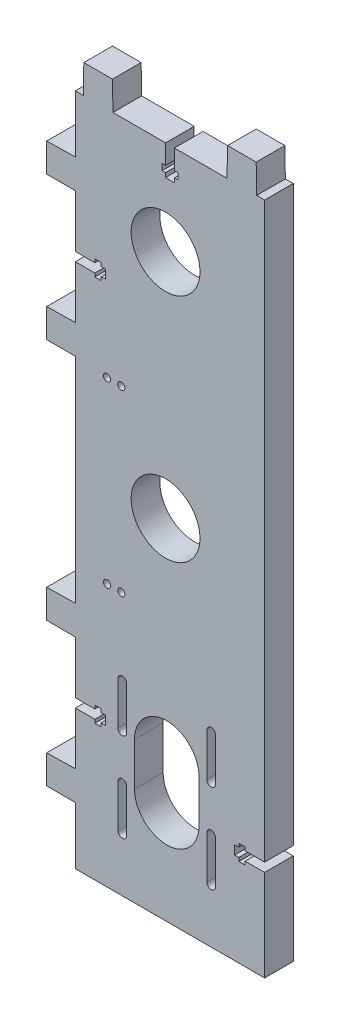
SolidWorks part; units mm, degrees
ref_plane "Front" through (0, 0, 0) normal (0, 0, 1) x (1, 0, 0)
ref_plane "Top" through (0, 0, 0) normal (0, 1, 0) x (1, 0, 0)
ref_plane "Right" through (0, 0, 0) normal (1, 0, 0) x (0, 0, -1)
sketch "Эскиз1" plane through (0, 0, 0) normal (0, 0, 1) x (1, 0, 0)
  line L0 (-204.2085, -30.606) -> (-138.2085, -30.606)
  line L1 (-214.2071, 124.2274) -> (-204.2085, 124.194)
  line L2 (-214.2071, 134.2274) -> (-214.2071, 124.2274)
  line L3 (-204.2085, 134.394) -> (-214.2071, 134.2274)
  line L4 (-204.2085, 152.744) -> (-204.2085, 134.394)
  line L5 (-197.4085, 152.744) -> (-204.2085, 152.744)
  line L6 (-197.4085, 151.544) -> (-197.4085, 152.744)
  line L7 (-195.2085, 151.544) -> (-197.4085, 151.544)
  line L8 (-195.2085, 152.744) -> (-195.2085, 151.544)
  line L9 (-193.7085, 152.744) -> (-195.2085, 152.744)
  line L10 (-193.7085, 155.844) -> (-193.7085, 152.744)
  line L11 (-195.2085, 155.844) -> (-193.7085, 155.844)
  line L12 (-195.2085, 157.044) -> (-195.2085, 155.844)
  line L13 (-197.4085, 157.044) -> (-195.2085, 157.044)
  line L14 (-197.4085, 155.844) -> (-197.4085, 157.044)
  line L15 (-204.2085, 155.844) -> (-197.4085, 155.844)
  line L16 (-204.2085, 174.194) -> (-204.2085, 155.844)
  line L17 (-214.2071, 174.2274) -> (-204.2085, 174.194)
  line L18 (-214.2071, 184.2274) -> (-214.2071, 174.2274)
  line L19 (-204.2085, 184.394) -> (-214.2071, 184.2274)
  line L20 (-214.2071, -10.5726) -> (-204.2085, -10.606)
  line L21 (-214.2071, -0.5726) -> (-214.2071, -10.5726)
  line L22 (-204.2085, -0.406) -> (-214.2071, -0.5726)
  line L23 (-204.2085, 17.944) -> (-204.2085, -0.406)
  line L24 (-197.4085, 17.944) -> (-204.2085, 17.944)
  line L25 (-197.4085, 16.744) -> (-197.4085, 17.944)
  line L26 (-195.2085, 16.744) -> (-197.4085, 16.744)
  line L27 (-195.2085, 17.944) -> (-195.2085, 16.744)
  line L28 (-193.7085, 17.944) -> (-195.2085, 17.944)
  line L29 (-193.7085, 21.044) -> (-193.7085, 17.944)
  line L30 (-195.2085, 21.044) -> (-193.7085, 21.044)
  line L31 (-195.2085, 22.244) -> (-195.2085, 21.044)
  line L32 (-197.4085, 22.244) -> (-195.2085, 22.244)
  line L33 (-197.4085, 21.044) -> (-197.4085, 22.244)
  line L34 (-204.2085, 21.044) -> (-197.4085, 21.044)
  line L35 (-204.2085, 39.394) -> (-204.2085, 21.044)
  line L36 (-214.2071, 39.4274) -> (-204.2085, 39.394)
  line L37 (-214.2071, 49.4274) -> (-214.2071, 39.4274)
  line L38 (-204.2085, 49.594) -> (-214.2071, 49.4274)
  line L39 (-201.2751, 214.3926) -> (-201.4418, 204.394)
  line L40 (-191.2751, 214.3926) -> (-201.2751, 214.3926)
  line L41 (-191.1085, 204.394) -> (-191.2751, 214.3926)
  line L42 (-172.7585, 204.394) -> (-191.1085, 204.394)
  line L43 (-172.7585, 197.594) -> (-172.7585, 204.394)
  line L44 (-173.9585, 197.594) -> (-172.7585, 197.594)
  line L45 (-173.9585, 195.394) -> (-173.9585, 197.594)
  line L46 (-172.7585, 195.394) -> (-173.9585, 195.394)
  line L47 (-172.7585, 193.894) -> (-172.7585, 195.394)
  line L48 (-169.6585, 193.894) -> (-172.7585, 193.894)
  line L49 (-169.6585, 195.394) -> (-169.6585, 193.894)
  line L50 (-168.4585, 195.394) -> (-169.6585, 195.394)
  line L51 (-168.4585, 197.594) -> (-168.4585, 195.394)
  line L52 (-169.6585, 197.594) -> (-168.4585, 197.594)
  line L53 (-169.6585, 204.394) -> (-169.6585, 197.594)
  line L54 (-151.3085, 204.394) -> (-169.6585, 204.394)
  line L55 (-151.1419, 214.3926) -> (-151.3085, 204.394)
  line L56 (-141.1419, 214.3926) -> (-151.1419, 214.3926)
  line L57 (-140.9752, 204.394) -> (-141.1419, 214.3926)
  line L58 (-204.2085, 204.394) -> (-201.4418, 204.394)
  line L59 (-140.9752, 204.394) -> (-138.2085, 204.394)
  line L60 (-204.2085, 204.394) -> (-204.2085, 184.394)
  line L61 (-204.2085, -30.606) -> (-204.2085, -10.606)
  line L62 (-204.2085, 124.194) -> (-204.2085, 49.594)
  line L63 (-145.0085, 4.394) -> (-138.2085, 4.394)
  line L64 (-145.0085, 5.594) -> (-145.0085, 4.394)
  line L65 (-147.2085, 5.594) -> (-145.0085, 5.594)
  line L66 (-147.2085, 4.394) -> (-147.2085, 5.594)
  line L67 (-148.7085, 4.394) -> (-147.2085, 4.394)
  line L68 (-148.7085, 1.294) -> (-148.7085, 4.394)
  line L69 (-147.2085, 1.294) -> (-148.7085, 1.294)
  line L70 (-147.2085, 0.094) -> (-147.2085, 1.294)
  line L71 (-145.0085, 0.094) -> (-147.2085, 0.094)
  line L72 (-145.0085, 1.294) -> (-145.0085, 0.094)
  line L73 (-138.2085, 1.294) -> (-145.0085, 1.294)
  line L74 (-138.2085, 204.394) -> (-138.2085, 4.394)
  line L75 (-138.2085, 1.294) -> (-138.2085, -30.606)
  line L76 (-186.3519, 19.2845) -> (-186.3519, 34.2845)
  line L77 (-189.3519, 19.2845) -> (-189.3519, 34.2845)
  line L78 (-155.3519, 19.2845) -> (-155.3519, 34.2845)
  line L79 (-158.3519, 19.2845) -> (-158.3519, 34.2845)
  line L80 (-155.3519, -11.7155) -> (-155.3519, 3.2845)
  line L81 (-158.3519, -11.7155) -> (-158.3519, 3.2845)
  line L82 (-186.3519, -11.7155) -> (-186.3519, 3.2845)
  line L83 (-189.3519, -11.7155) -> (-189.3519, 3.2845)
  line L84 (-183.6019, 3.7845) -> (-183.6019, 18.7845)
  line L85 (-161.1019, 3.7845) -> (-161.1019, 18.7845)
  arc A0 (-189.3519, -11.7155) -> (-186.3519, -11.7155) centre (-187.8519, -11.7155) ccw
  arc A1 (-189.3519, 19.2845) -> (-186.3519, 19.2845) centre (-187.8519, 19.2845) ccw
  arc A2 (-183.6019, 3.7845) -> (-161.1019, 3.7845) centre (-172.3519, 3.7845) ccw
  arc A3 (-158.3519, 19.2845) -> (-155.3519, 19.2845) centre (-156.8519, 19.2845) ccw
  arc A4 (-158.3519, -11.7155) -> (-155.3519, -11.7155) centre (-156.8519, -11.7155) ccw
  circle A5 centre (-172.7585, 171.4708) radius 12
  circle A6 centre (-172.7585, 90.9484) radius 12
  circle A7 centre (-188.185, 60.9096) radius 1.25
  circle A8 centre (-193.1563, 60.9774) radius 1.25
  circle A9 centre (-188.2043, 123.1993) radius 1.25
  circle A10 centre (-193.1757, 123.2672) radius 1.25
  arc A11 (-186.3519, 34.2845) -> (-189.3519, 34.2845) centre (-187.8519, 34.2845) ccw
  arc A12 (-155.3519, 34.2845) -> (-158.3519, 34.2845) centre (-156.8519, 34.2845) ccw
  arc A13 (-161.1019, 18.7845) -> (-183.6019, 18.7845) centre (-172.3519, 18.7845) ccw
  arc A14 (-186.3519, 3.2845) -> (-189.3519, 3.2845) centre (-187.8519, 3.2845) ccw
  arc A15 (-155.3519, 3.2845) -> (-158.3519, 3.2845) centre (-156.8519, 3.2845) ccw
extrude "Бобышка-Вытянуть1" add sketch "Эскиз1" along normal blind 10
